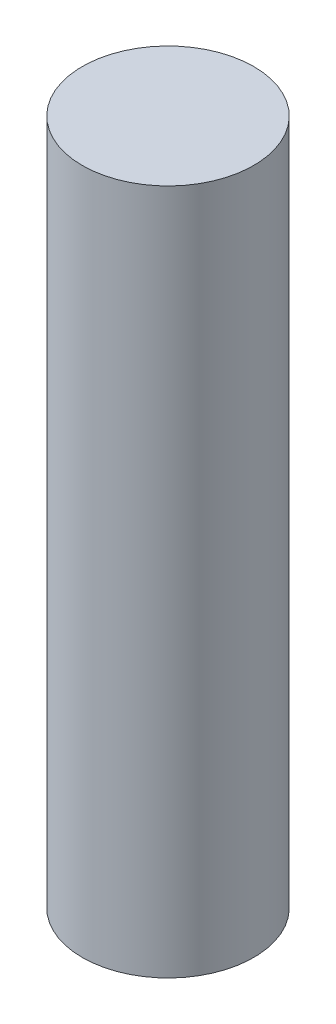
SolidWorks part; units mm, degrees
ref_plane "정면" through (0, 0, 0) normal (0, 0, 1) x (1, 0, 0)
ref_plane "윗면" through (0, 0, 0) normal (0, 1, 0) x (1, 0, 0)
ref_plane "우측면" through (0, 0, 0) normal (1, 0, 0) x (0, 0, -1)
sketch "스케치1" plane through (0, 0, 0) normal (0, 1, 0) x (1, 0, 0)
  circle A0 centre (0, 0) radius 5
  dimension "D1" = 10
extrude "보스-돌출1" add sketch "스케치1" along normal blind 40
